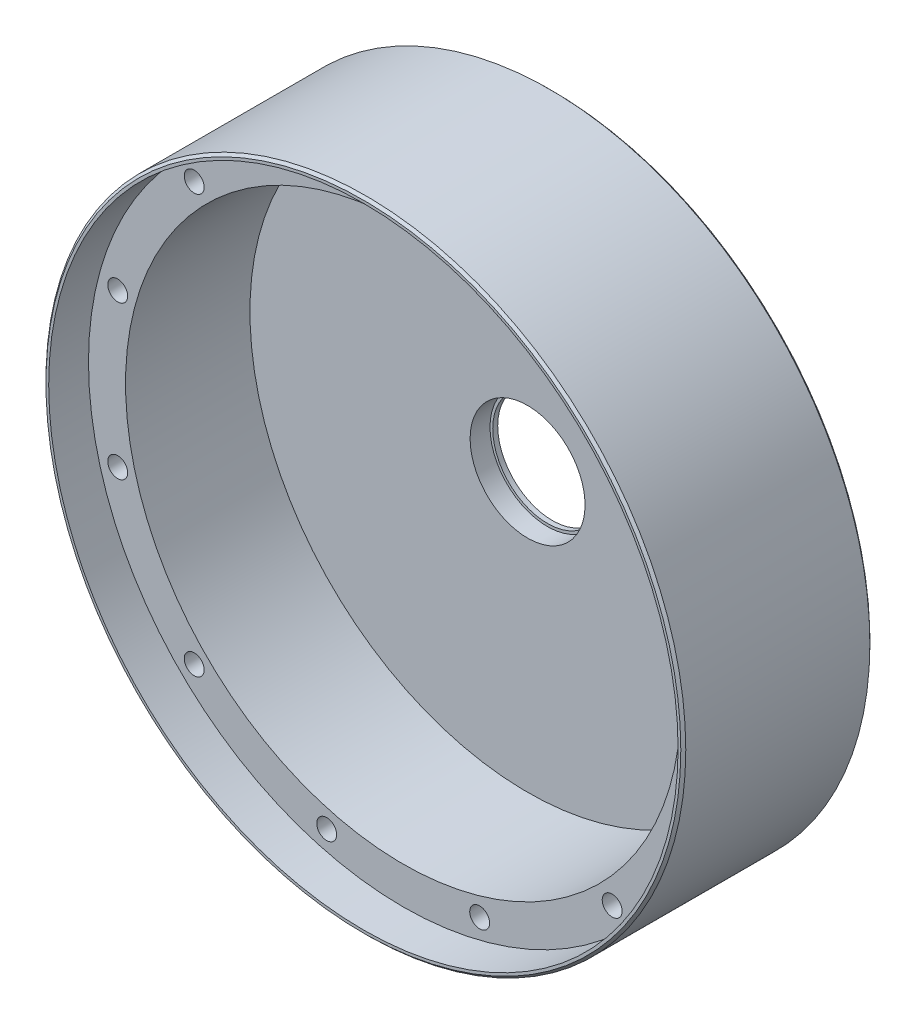
SolidWorks part; units mm, degrees
material "ABS"
ref_plane "Front Plane" through (0, 0, 0) normal (0, 0, 1) x (1, 0, 0)
ref_plane "Top Plane" through (0, 0, 0) normal (0, 1, 0) x (1, 0, 0)
ref_plane "Right Plane" through (0, 0, 0) normal (1, 0, 0) x (0, 0, -1)
sketch "Actuator Housing Mount" plane through (0, 0, 19) normal (0, 0, 1) x (1, 0, 0)
  line L0 (0, 0) -> (63, 0) construction
  line L1 (0, 0) -> (62.0607, 16.6291) construction
  circle A1 centre (57.376, 15.3739) radius 3.6 construction
  circle A2 centre (0, 0) radius 55.8
  circle A3 centre (57.376, 15.3739) radius 1.55
  circle A4 centre (57.376, -15.3739) radius 1.55
  circle A5 centre (42.0021, -42.0021) radius 1.55
  circle A6 centre (15.3739, -57.376) radius 1.55
  circle A7 centre (-15.3739, -57.376) radius 1.55
  circle A8 centre (-42.0021, -42.0021) radius 1.55
  circle A9 centre (-57.376, -15.3739) radius 1.55
  circle A10 centre (-57.376, 15.3739) radius 1.55
  circle A11 centre (-42.0021, 42.0021) radius 1.55
  circle A12 centre (-15.3739, 57.376) radius 1.55
  circle A13 centre (15.3739, 57.376) radius 1.55
  circle A14 centre (42.0021, 42.0021) radius 1.55
  circle A15 centre (0, 0) radius 64.3
  point P13 (0, 0)
  point P35 (0, 0)
  point P36 (0, 0)
  point P37 (63, 16.8789)
  point P38 (62.1584, 16.6553)
  point P39 (63, 16.8786)
  point P40 (63.9964, 17.1478)
  point P41 (63.7616, 17.0849)
extrude "Actuator Housing Wall" add sketch "Actuator Housing Mount" against normal blind 25
sketch "Sketch2" plane through (0, 0, -6) normal (0, 0, -1) x (-1, 0, 0)
  circle A0 centre (0, 0) radius 64.3
  circle A1 centre (0, 0) radius 64.3 construction
  circle M2 centre (-42.0021, 42.0021) radius 1.55
  circle M3 centre (-15.3739, 57.376) radius 1.55
  circle M4 centre (15.3739, 57.376) radius 1.55
  circle M5 centre (42.0021, 42.0021) radius 1.55
  circle M6 centre (57.376, 15.3739) radius 1.55
  circle M7 centre (57.376, -15.3739) radius 1.55
  circle M8 centre (42.0021, -42.0021) radius 1.55
  circle M9 centre (15.3739, -57.376) radius 1.55
  circle M10 centre (-15.3739, -57.376) radius 1.55
  circle M11 centre (-42.0021, -42.0021) radius 1.55
  circle M12 centre (0, 0) radius 55.8
  circle M13 centre (-57.376, -15.3739) radius 1.55
  circle M14 centre (-57.376, 15.3739) radius 1.55
  circle M15 centre (0, 0) radius 64.3
extrude "Boss-Extrude2" add sketch "Sketch2" along normal blind 5 contours M15 M3 M5 M7 M9 M11 M13 M14 M12 M10 M8 M6 M4 M2 | M12
sketch "Sketch3" plane through (0, 0, -11) normal (0, 0, -1) x (-1, 0, 0)
  circle A0 centre (0, 0) radius 11.55
  dimension "D1" = 23.1
extrude "Cut-Extrude1" cut sketch "Sketch3" along normal blind 4 from surface at -5 starting at face at (55.8, 0, -6)
sketch "Sketch4" plane through (0, 0, -11) normal (0, 0, -1) x (-1, 0, 0)
  circle A0 centre (0, 0) radius 11
  dimension "D1" = 22
extrude "Cut-Extrude2" cut sketch "Sketch4" against normal blind 4
sketch "Sketch6" plane through (0, 0, 19) normal (0, 0, 1) x (1, 0, 0)
  circle A0 centre (0, 0) radius 64.3
  circle A1 centre (0, 0) radius 63.25
  dimension "D1" = 128.6
  dimension "D2" = 126.5
extrude "Boss-Extrude3" add sketch "Sketch6" along normal blind 8
sketch "Sketch7" plane through (0, 0, 19) normal (0, 0, 1) x (1, 0, 0)
  circle A0 centre (57.376, -15.3739) radius 2
  circle A1 centre (42.0021, -42.0021) radius 2
  circle A2 centre (15.3739, -57.376) radius 2
  circle A3 centre (-15.3739, -57.376) radius 2
  circle A4 centre (-42.0021, -42.0021) radius 2
  circle A5 centre (-57.376, -15.3739) radius 2
  circle A6 centre (-57.376, 15.3739) radius 2
  circle A7 centre (-42.0021, 42.0021) radius 2
  circle A8 centre (-15.3739, 57.376) radius 2
  circle A9 centre (15.3739, 57.376) radius 2
  circle A10 centre (42.0021, 42.0021) radius 2
  circle A11 centre (57.376, 15.3739) radius 2
  point P3 (57.376, 15.3739)
  point P27 (0, 0)
  dimension "D1" = 12
  dimension "M3 Insert" = 4
extrude "M3 Insert L12" cut sketch "Sketch7" against normal blind 12
chamfer "Chamfer2" distance 0.5 angle 45 2 edges at (64.3, 0, 27) (-64.3, 0, -11)
